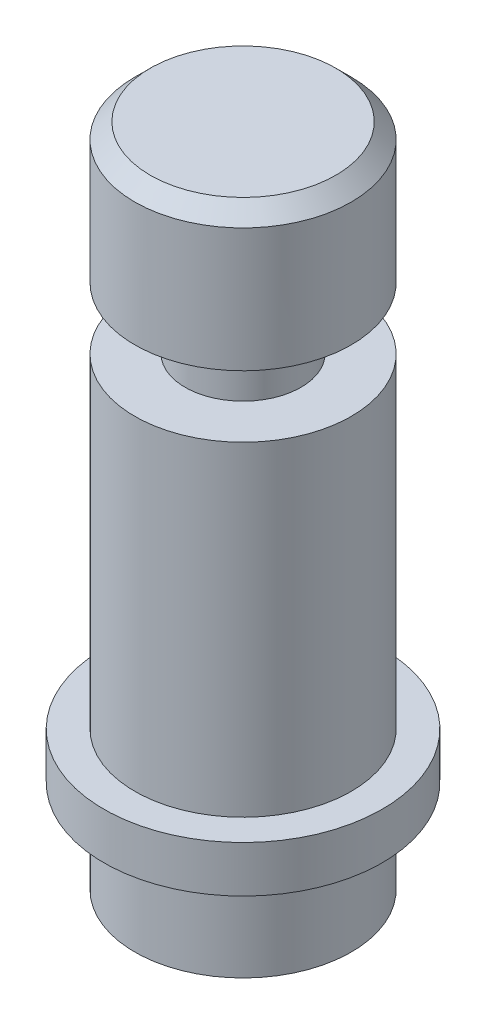
SolidWorks part; units mm, degrees
material "AISI 1035 Steel (SS)"
ref_plane "Front Plane" through (0, 0, 0) normal (0, 0, 1) x (1, 0, 0)
ref_plane "Top Plane" through (0, 0, 0) normal (0, 1, 0) x (1, 0, 0)
ref_plane "Right Plane" through (0, 0, 0) normal (1, 0, 0) x (0, 0, -1)
sketch "Sketch1" plane through (0, 0, 0) normal (0, 0, 1) x (1, 0, 0)
  line L0 (0, 0) -> (0, 43) construction
  line L1 (0, 0) -> (7, 0)
  line L2 (7, 0) -> (7, 6)
  line L3 (7, 6) -> (9, 6)
  line L4 (9, 6) -> (9, 9)
  line L5 (9, 9) -> (7, 9)
  line L6 (7, 9) -> (7, 30)
  line L7 (7, 30) -> (3.75, 30)
  line L8 (3.75, 30) -> (3.75, 34)
  line L9 (3.75, 34) -> (7, 34)
  line L10 (7, 34) -> (7, 43)
  line L11 (7, 43) -> (0, 43)
  line L12 (0, 43) -> (0, 0)
  dimension "D1" = 43
  dimension "D2" = 14
  dimension "D3" = 14
  dimension "D4" = 7.5
  dimension "D5" = 18
  dimension "D6" = 14
  dimension "D7" = 4
  dimension "D8" = 9
  dimension "D9" = 25
  dimension "D10" = 3
revolve "Main Body" add sketch "Sketch1" angle 360 about L0
chamfer "Top Chamfer" distance 1 angle 45 1 edges at (0, 43, -7)
